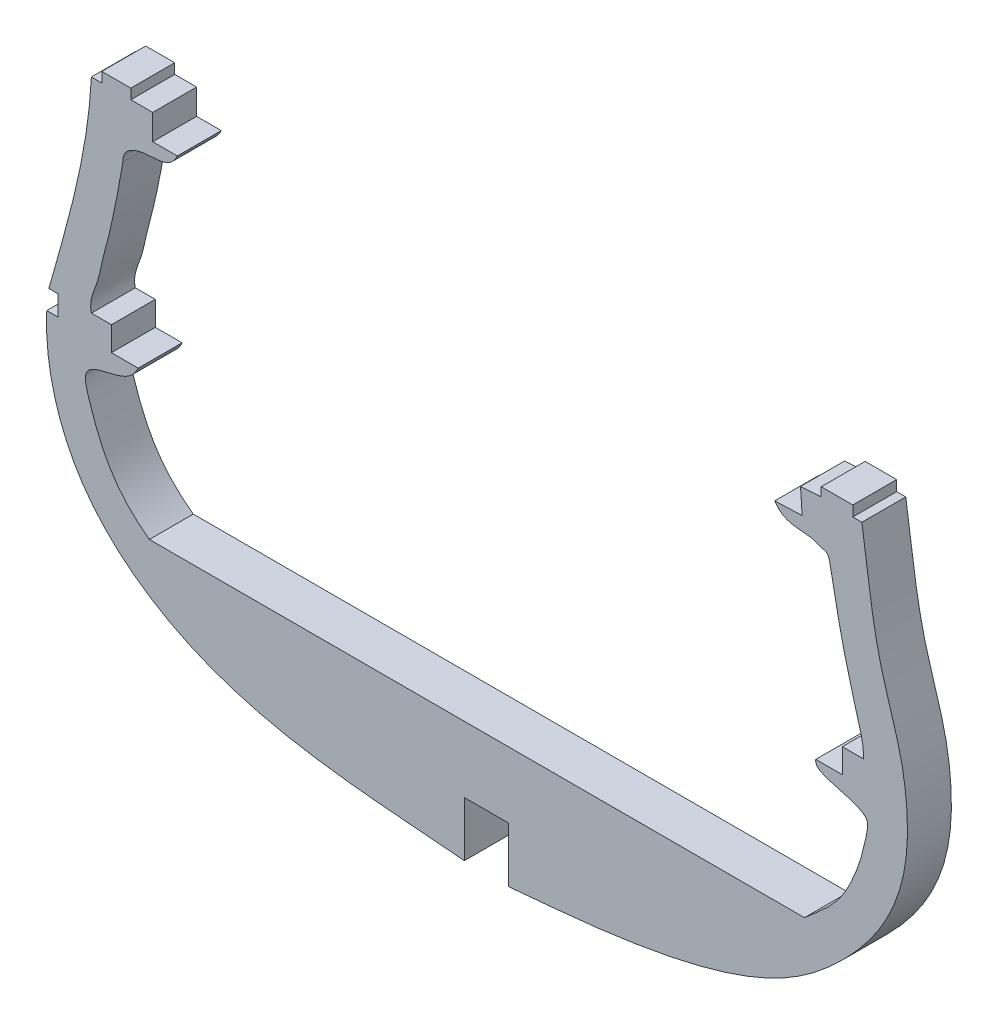
SolidWorks part; units mm, degrees
ref_plane "前视基准面" through (0, 0, 0) normal (0, 0, 1) x (1, 0, 0)
ref_plane "上视基准面" through (0, 0, 0) normal (0, 1, 0) x (1, 0, 0)
ref_plane "右视基准面" through (0, 0, 0) normal (1, 0, 0) x (0, 0, -1)
other "Configuration Table"
sketch "草图1" plane through (0, 0, 0) normal (0, 0, 1) x (1, 0, 0)
  line L0 (556.8633, 460.8086) -> (1980.8143, -29.4971) construction
  line L1 (1817.4837, -493.8259) -> (1936.7955, -493.8259)
  line L2 (1874.8505, -515.8154) -> (1874.8505, -505.8475)
  line L4 (1882.8495, -505.8475) -> (1882.8495, -515.8858)
  line L5 (1938.8547, -467.8263) -> (1943.6822, -467.8263)
  line L6 (1943.6822, -467.8263) -> (1943.6822, -463.4086)
  line L7 (1943.6822, -463.4086) -> (1947.5079, -463.4086)
  line L8 (1931.3772, -430.7903) -> (1936.3747, -430.6072)
  line L9 (1936.3747, -430.6072) -> (1936.0817, -426.1612)
  line L10 (1936.0817, -426.1612) -> (1939.8546, -425.9126)
  line L11 (1939.8546, -425.9126) -> (1939.8546, -424.3276)
  line L12 (1939.8546, -424.3276) -> (1945.595, -424.3276)
  line L13 (1945.595, -424.3276) -> (1945.595, -426.2316)
  line L14 (1945.595, -426.2316) -> (1947.2456, -426.2316)
  line L15 (1798.7931, -467.0672) -> (1800.8196, -467.0672)
  line L16 (1800.8196, -467.0672) -> (1800.8196, -463.4086)
  line L17 (1800.8196, -463.4086) -> (1799.178, -463.4086)
  line L18 (1806.9187, -426.1612) -> (1808.814, -426.1612)
  line L19 (1808.814, -426.1612) -> (1808.814, -424.3276)
  line L20 (1808.814, -424.3276) -> (1814.1011, -424.3276)
  line L21 (1814.1011, -424.3276) -> (1814.1011, -426.1612)
  line L22 (1814.1011, -426.1612) -> (1818.0913, -426.1612)
  line L23 (1818.0913, -426.1612) -> (1818.0913, -430.7903)
  line L24 (1818.0913, -430.7903) -> (1822.5802, -430.7903)
  line L25 (1806.9187, -463.4086) -> (1810.5688, -463.4086)
  line L26 (1810.5688, -463.4086) -> (1810.5688, -467.8263)
  line L27 (1810.5688, -467.8263) -> (1815.4476, -467.8263)
  line L28 (1874.8505, -505.8475) -> (1882.8495, -505.8475)
  spline S0 degree 3 poles (1936.7955, -493.8259) (1939.7472, -491.1765) (1944.2876, -488.0111) (1947.2758, -479.0186) (1947.5079, -477.5725) knots 0 0 0 0 0.565523 1 1 1 1
  spline S1 degree 3 poles (1938.8547, -467.8263) (1938.7472, -468.7906) (1940.0827, -469.518) (1942.9288, -470.4532) (1945.7058, -470.9702) (1948.4799, -472.56) (1948.145, -475.0396) (1947.8446, -476.4456) (1947.5079, -477.5725) knots 0 0 0 0 0.139252 0.269941 0.567642 0.702119 0.78821 1 1 1 1
  spline S2 degree 3 poles (1947.5079, -463.4086) (1947.6441, -461.4952) (1946.5202, -457.5004) (1944.5134, -450.5909) (1942.8146, -442.9866) (1941.8714, -437.5967) (1941.1268, -434.1209) (1939.7909, -433.9511) (1938.7808, -433.4222) (1935.7448, -432.8218) (1933.0085, -433.2468) (1931.3772, -430.7903) knots 0 0 0 0 0.141972 0.305068 0.542473 0.707536 0.747503 0.772219 0.79896 0.833581 1 1 1 1
  spline S3 degree 3 poles (1947.2456, -426.2316) (1948.3666, -433.2044) (1949.3748, -445.0317) (1954.3829, -458.219) (1956.7796, -476.3541) (1952.9, -489.099) (1936.4797, -503.6239) (1916.9279, -513.8066) (1890.6956, -515.0447) (1882.8495, -515.8858) knots 0 0 0 0 0.167479 0.276197 0.331934 0.591851 0.630174 0.715161 1 1 1 1
  spline S4 degree 3 poles (1798.7931, -467.0672) (1798.3739, -475.4835) (1802.572, -491.6526) (1830.1139, -513.7378) (1857.2626, -514.2195) (1874.8505, -515.8154) knots 0 0 0 0 0.251171 0.460842 1 1 1 1
  spline S5 degree 3 poles (1799.178, -463.4086) (1802.6101, -451.2028) (1806.3156, -438.9199) (1806.9187, -426.1612) knots 0 0 0 0 1 1 1 1
  spline S6 degree 3 poles (1806.9187, -463.4086) (1806.4361, -461.3914) (1808.0303, -458.6537) (1808.8466, -454.1903) (1810.7936, -447.244) (1811.8681, -441.2147) (1812.6614, -436.6792) knots 0 0 0 0 0.211182 0.331085 0.496002 1 1 1 1
  spline S7 degree 3 poles (1812.6614, -436.6792) (1812.5941, -434.6719) (1816.8165, -432.4739) (1821.1743, -433.7914) (1822.5802, -430.7903) knots 0 0 0 0 0.403935 1 1 1 1
  spline S8 degree 3 poles (1817.4837, -493.8259) (1811.476, -489.4643) (1808.272, -483.5646) (1805.1667, -472.7663) (1810.6549, -470.8303) (1814.1139, -470.7065) (1815.4476, -467.8263) knots 0 0 0 0 0.575038 0.69362 0.776965 1 1 1 1
  dimension "D3" = 10.0384
extrude "凸台-拉伸1" add sketch "草图1" along normal blind 8
